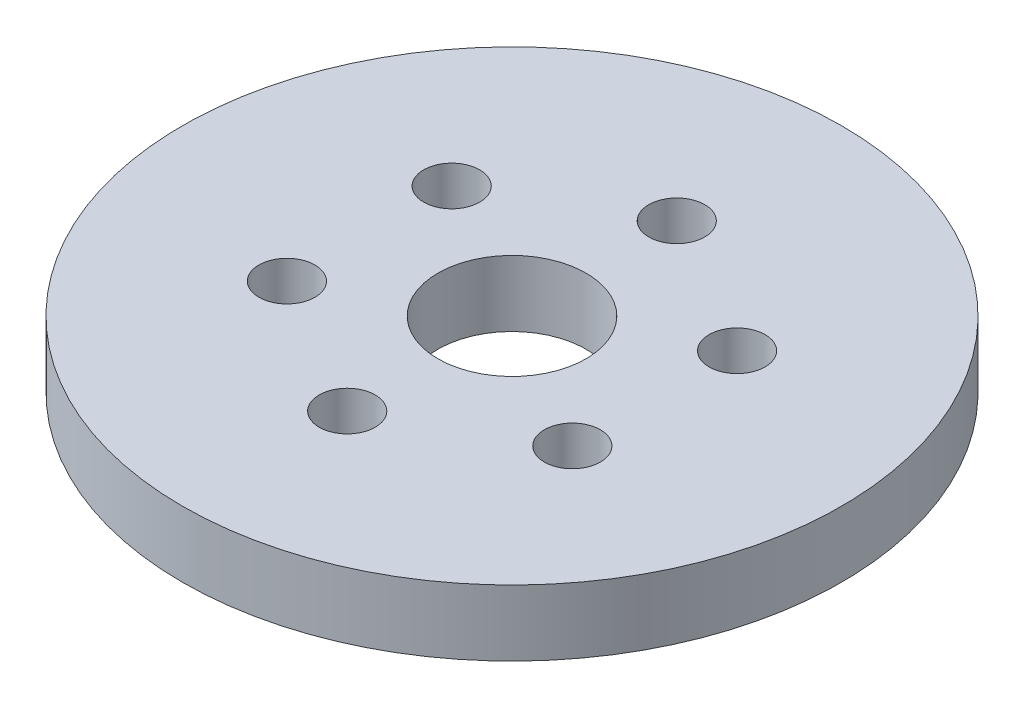
SolidWorks part; units mm, degrees
ref_plane "前视基准面" through (0, 0, 0) normal (0, 0, 1) x (1, 0, 0)
ref_plane "上视基准面" through (0, 0, 0) normal (0, 1, 0) x (1, 0, 0)
ref_plane "右视基准面" through (0, 0, 0) normal (1, 0, 0) x (0, 0, -1)
sketch "草图1" plane through (0, 0, 0) normal (0, 1, 0) x (1, 0, 0)
  circle A0 centre (0, 0) radius 20
  circle A1 centre (0, 0) radius 4.5
  dimension "D1" = 40
  dimension "D2" = 9
extrude "凸台-拉伸1" add sketch "草图1" along normal blind 4
sketch "草图2" plane through (0, 4, 0) normal (0, 1, 0) x (1, 0, 0)
  line L0 (0, -10) -> (0, 10) construction
  circle A0 centre (0, 0) radius 10 construction
  circle A1 centre (0, 10) radius 1.7
  circle A2 centre (0, 0) radius 10 construction
  circle A3 centre (8.6603, 5) radius 1.7
  circle A4 centre (0, 0) radius 10 construction
  circle A5 centre (8.6603, -5) radius 1.7
  circle A6 centre (0, 0) radius 10 construction
  circle A7 centre (0, -10) radius 1.7
  circle A8 centre (0, 0) radius 10 construction
  circle A9 centre (-8.6603, -5) radius 1.7
  circle A10 centre (0, 0) radius 10 construction
  circle A11 centre (-8.6603, 5) radius 1.7
  point P23 (0, 0)
  dimension "D1" = 20
  dimension "D2" = 3.4
  dimension "D3" = 6
extrude "切除-拉伸1" cut sketch "草图2" against normal through all
